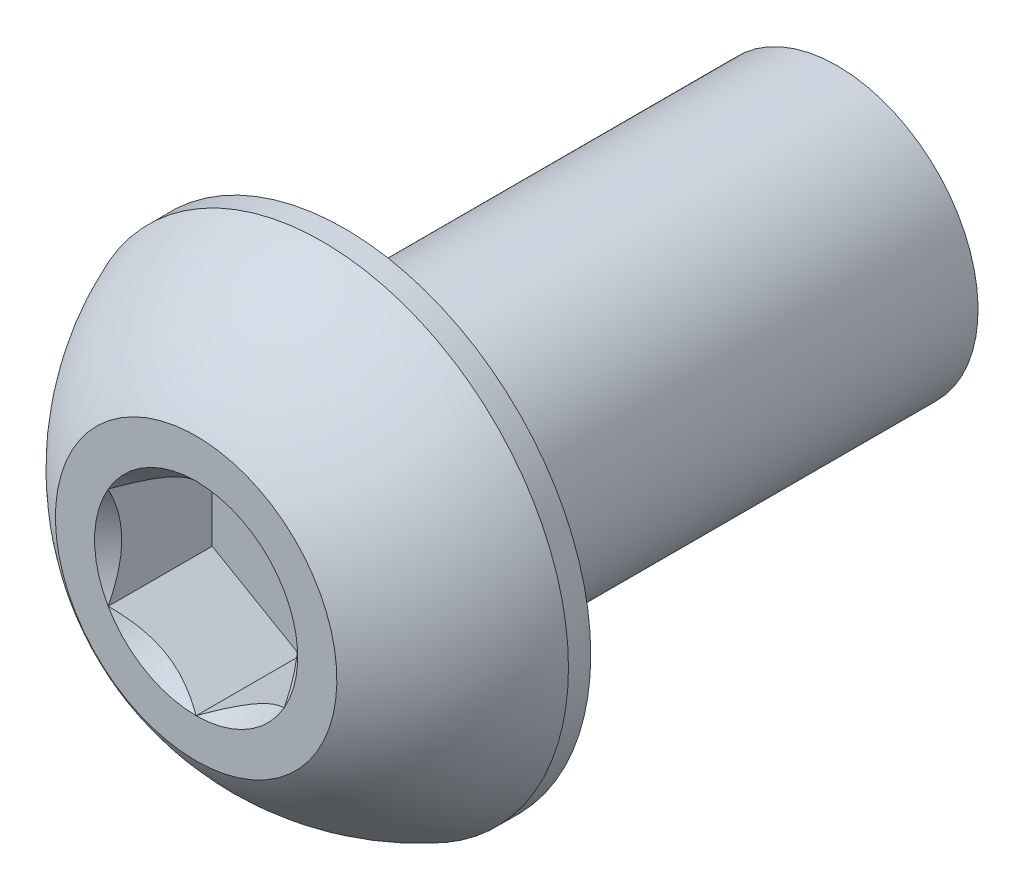
SolidWorks part; units mm, degrees
material "Chrome Stainless Steel"
ref_plane "Front" through (0, 0, 0) normal (0, 0, 1) x (1, 0, 0)
ref_plane "Top" through (0, 0, 0) normal (0, 1, 0) x (1, 0, 0)
ref_plane "Right" through (0, 0, 0) normal (1, 0, 0) x (0, 0, -1)
sketch "Sketch1" plane through (0, 0, 0) normal (1, 0, 0) x (0, 0, -1)
  line L2 (3.3528, 3.175) -> (14.4653, 3.175)
  line L3 (14.4653, 3.175) -> (14.4653, 0)
  line L4 (14.4653, 0) -> (3.3528, 0)
  line L6 (2.8499, 5.5499) -> (3.3528, 5.5499) construction
  line L7 (14.4653, 3.175) -> (14.4653, -3.175) construction
  line L8 (0, 0) -> (3.3528, 0) construction
  line L9 (3.3528, 5.5499) -> (3.3528, -5.5499) construction
  line L11 (3.3528, 3.175) -> (3.3528, 0)
  line L13 (0, 1.9844) -> (0, -1.9844) construction
  line L14 (0, 1.9844) -> (0, 3.175) construction
  arc A3 (0, 3.175) -> (2.8499, 5.5499) centre (5.0603, 0) cw construction
  dimension "D1" = 0.5029
revolve "Revolve1" add sketch "Sketch1" angle 360 mid plane about L4
sketch "Sketch3" plane through (0, 0, -14.4653) normal (0, 0, -1) x (-1, 0, 0)
  circle A0 centre (0, 0) radius 3.175
sketch "Sketch2" plane through (0, 0, 0) normal (1, 0, 0) x (0, 0, -1)
  line L0 (14.4653, 3.175) -> (15.5765, 3.175)
  line L1 (15.5765, 3.175) -> (15.1003, 2.3501)
  line L2 (15.1003, 2.3501) -> (14.9415, 2.3501)
  line L3 (14.9415, 2.3501) -> (14.4653, 3.175)
  line L4 (14.7034, 2.7626) -> (15.3384, 2.7626) construction
  dimension "D1" = 60
  dimension "D2" = 0.1588
  dimension "D3" = 0.635
sketch "Sketch7" plane through (0, 0, 0) normal (1, 0, 0) x (0, 0, -1)
  line L6 (2.8499, 5.5499) -> (3.3528, 5.5499) construction
  line L8 (0, 0) -> (3.3528, 0) construction
  line L11 (3.3528, 5.5499) -> (3.3528, -5.5499) construction
  line L12 (2.8499, 5.5499) -> (3.3528, 5.5499)
  line L13 (0, 0) -> (3.3528, 0)
  line L14 (0, 1.9844) -> (0, -1.9844) construction
  line L15 (3.3528, 5.5499) -> (3.3528, 0)
  line L16 (0, 3.175) -> (0, 0)
  arc A2 (2.8499, 5.5499) -> (0, 3.175) centre (5.0603, 0) ccw construction
  arc A3 (2.8499, 5.5499) -> (0, 3.175) centre (5.0603, 0) ccw
revolve "Revolve2" add sketch "Sketch7" angle 360 mid plane about L13
sketch "Sketch5" plane through (0, 0, 0) normal (0, 0, 1) x (1, 0, 0)
  line L1 (1.9844, -1.1457) -> (1.9844, 1.1457)
  line L2 (1.9844, 1.1457) -> (0, 2.2914)
  line L3 (0, 2.2914) -> (-1.9844, 1.1457)
  line L4 (-1.9844, 1.1457) -> (-1.9844, -1.1457)
  line L5 (-1.9844, -1.1457) -> (0, -2.2914)
  line L6 (0, -2.2914) -> (1.9844, -1.1457)
  circle A0 centre (0, 0) radius 1.9844 construction
extrude "Cut-Extrude2" cut sketch "Sketch5" against normal blind 2.347
sketch "Sketch6" plane through (0, 0, 0) normal (0, 0, 1) x (1, 0, 0)
  circle A0 centre (0, 0) radius 2.2914
extrude "Cut-Extrude3" cut sketch "Sketch6" against normal blind 2.347 draft 45
equation "\"D1@Cut-Extrude2\" = \"Head Ht@Sketch1\" * .7"
equation "\"D1@Sketch1\" = \"Head Ht@Sketch1\" * .15"
equation "\"D1@Cut-Extrude3\" = \"D1@Cut-Extrude2\""
